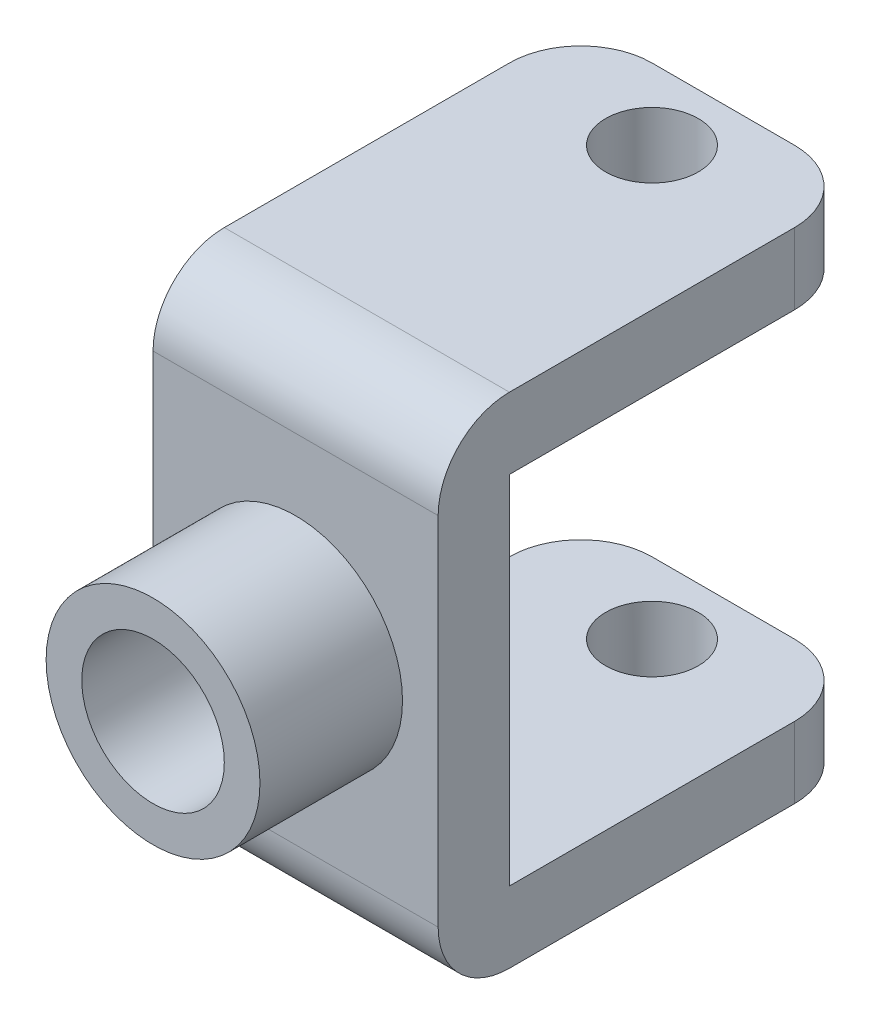
SolidWorks part; units mm, degrees
ref_plane "Front Plane" through (0, 0, 0) normal (0, 0, 1) x (1, 0, 0)
ref_plane "Top Plane" through (0, 0, 0) normal (0, 1, 0) x (1, 0, 0)
ref_plane "Right Plane" through (0, 0, 0) normal (1, 0, 0) x (0, 0, -1)
sketch "Sketch1" plane through (0, 0, 0) normal (0, 0, 1) x (1, 0, 0)
  line L1 (-20, -25) -> (20, -25)
  line L2 (-20, -25) -> (-20, 25)
  line L3 (-20, 25) -> (20, 25)
  line L4 (20, -25) -> (20, 25)
  line L5 (-20, -25) -> (20, 25) construction
  line L6 (-20, 25) -> (20, -25) construction
  point P0 (0, 0)
  dimension "D1" = 40
  dimension "D2" = 50
extrude "Boss-Extrude1" add sketch "Sketch1" along normal blind 10
sketch "Sketch2" plane through (0, 0, 0) normal (1, 0, 0) x (0, 0, -1)
  line L1 (-10, 25) -> (50, 25)
  line L2 (-10, 25) -> (-10, 35)
  line L3 (-10, 35) -> (50, 35)
  line L4 (50, 25) -> (50, 35)
  line L5 (-10, -25) -> (50, -25)
  line L6 (-10, -25) -> (-10, -35)
  line L7 (-10, -35) -> (50, -35)
  line L8 (50, -25) -> (50, -35)
  dimension "D1" = 60
  dimension "D2" = 60
  dimension "D3" = 10
  dimension "D4" = 10
extrude "Boss-Extrude2" add sketch "Sketch2" along normal mid plane 40
fillet "Fillet1" radius 10 6 edges at (0, 35, 10) (0, -35, 10) (-20, -30, -50) (20, -30, -50) (-20, 30, -50) (20, 30, -50)
sketch "Sketch3" plane through (0, 0, 10) normal (0, 0, 1) x (1, 0, 0)
  circle A0 centre (0, 0) radius 15
  circle A1 centre (0, 0) radius 10
  dimension "D1" = 30
  dimension "D2" = 20
extrude "Boss-Extrude3" add sketch "Sketch3" along normal blind 20
sketch "Sketch4" plane through (0, 35, 0) normal (0, 1, 0) x (1, 0, 0)
  line L0 (10, 50) -> (-10, 50) construction
  circle A0 centre (0, 40) radius 6.5
  dimension "D1" = 10
  dimension "D2" = 13
extrude "Cut-Extrude1" cut sketch "Sketch4" against normal through all
